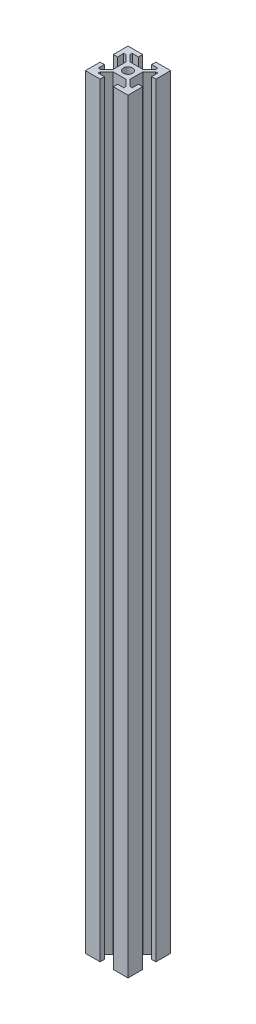
SolidWorks part; units mm, degrees
ref_plane "Front" through (0, 0, 0) normal (0, 0, 1) x (1, 0, 0)
ref_plane "Top" through (0, 0, 0) normal (0, 1, 0) x (1, 0, 0)
ref_plane "Right" through (0, 0, 0) normal (1, 0, 0) x (0, 0, -1)
sketch "스케치1" plane through (0, 0, 0) normal (0, 1, 0) x (1, 0, 0)
  line L0 (3.1, 8) -> (6, 8)
  line L1 (-10.001, 9.999) -> (-3.1, 9.999)
  line L2 (-10.001, 9.999) -> (-10.001, 3.1)
  line L3 (-10.001, -9.999) -> (-3.1, -9.999)
  line L4 (10.001, 9.999) -> (10.001, 3.1)
  line L5 (-10.001, 9.999) -> (-1.5204, 1.5201) construction
  line L6 (-10.001, -9.999) -> (-1.5204, -1.5201) construction
  line L11 (-7, -7) -> (-1.5203, -1.5203) construction
  line L12 (-7, 7) -> (-1.5203, 1.5203) construction
  line L15 (-3.1, 9.999) -> (-3.1, 8)
  line L17 (3.1, 9.999) -> (3.1, 8)
  line L18 (8, -3.1) -> (8, -6)
  line L27 (-3.1, 8) -> (-6, 8)
  line L28 (6, 8) -> (6, 7)
  line L30 (0, 4) -> (3, 4)
  line L31 (3, 4) -> (6, 7)
  line L32 (-6, 8) -> (-6, 7)
  line L33 (-6, 7) -> (-3, 4)
  line L34 (0, 4) -> (-3, 4)
  line L35 (3.1, 9.999) -> (10.001, 9.999)
  line L36 (10.001, 3.1) -> (8, 3.1)
  line L37 (10.001, -3.1) -> (8, -3.1)
  line L38 (8, 3.1) -> (8, 6)
  line L39 (8, -6) -> (7, -6)
  line L40 (4, 0) -> (4, -3)
  line L41 (4, -3) -> (7, -6)
  line L42 (8, 6) -> (7, 6)
  line L43 (7, 6) -> (4, 3)
  line L44 (4, 0) -> (4, 3)
  line L45 (-3.1, -8) -> (-6, -8)
  line L47 (3.1, -9.999) -> (3.1, -8)
  line L48 (-3.1, -9.999) -> (-3.1, -8)
  line L49 (3.1, -8) -> (6, -8)
  line L50 (-6, -8) -> (-6, -7)
  line L51 (0, -4) -> (-3, -4)
  line L52 (-3, -4) -> (-6, -7)
  line L53 (6, -8) -> (6, -7)
  line L54 (6, -7) -> (3, -4)
  line L55 (0, -4) -> (3, -4)
  line L56 (-8, 3.1) -> (-8, 6)
  line L58 (-10.001, -3.1) -> (-8, -3.1)
  line L59 (-10.001, 3.1) -> (-8, 3.1)
  line L60 (-8, -3.1) -> (-8, -6)
  line L61 (-8, 6) -> (-7, 6)
  line L62 (-4, 0) -> (-4, 3)
  line L63 (-4, 3) -> (-7, 6)
  line L64 (-8, -6) -> (-7, -6)
  line L65 (-7, -6) -> (-4, -3)
  line L66 (-4, 0) -> (-4, -3)
  line L67 (-10.001, -3.1) -> (-10.001, -9.999)
  line L69 (3.1, -9.999) -> (10.001, -9.999)
  line L72 (10.001, -3.1) -> (10.001, -9.999)
  line L73 (1.5203, -1.5203) -> (7, -7) construction
  line L74 (1.5204, -1.5201) -> (10.001, -9.999) construction
  line L75 (1.5203, 1.5203) -> (7, 7) construction
  line L76 (1.5204, 1.5201) -> (10.001, 9.999) construction
  circle A4 centre (0, 0) radius 2.15
  point P0 (0, 0)
  point P6 (0, 0)
  point P21 (0, 0)
  point P22 (0, 10)
  point P31 (0, 0)
  point P40 (10, 0)
  point P46 (0, 0)
  point P53 (0, -10)
  point P59 (0, 0)
  point P66 (-10, 0)
  point P72 (0, 0)
  dimension "D1" = 4
extrude "보스-돌출1" add sketch "스케치1" along normal blind 359
sketch "스케치3" plane through (10.001, 0, 0) normal (1, 0, 0) x (0, 0, -1)
  line L0 (0, 0) -> (0, 359) construction
  line L1 (-3, 359) -> (3, 359) construction
  circle A0 centre (0, 179.5) radius 3
extrude "컷-돌출1" cut sketch "스케치3" against normal blind 26
